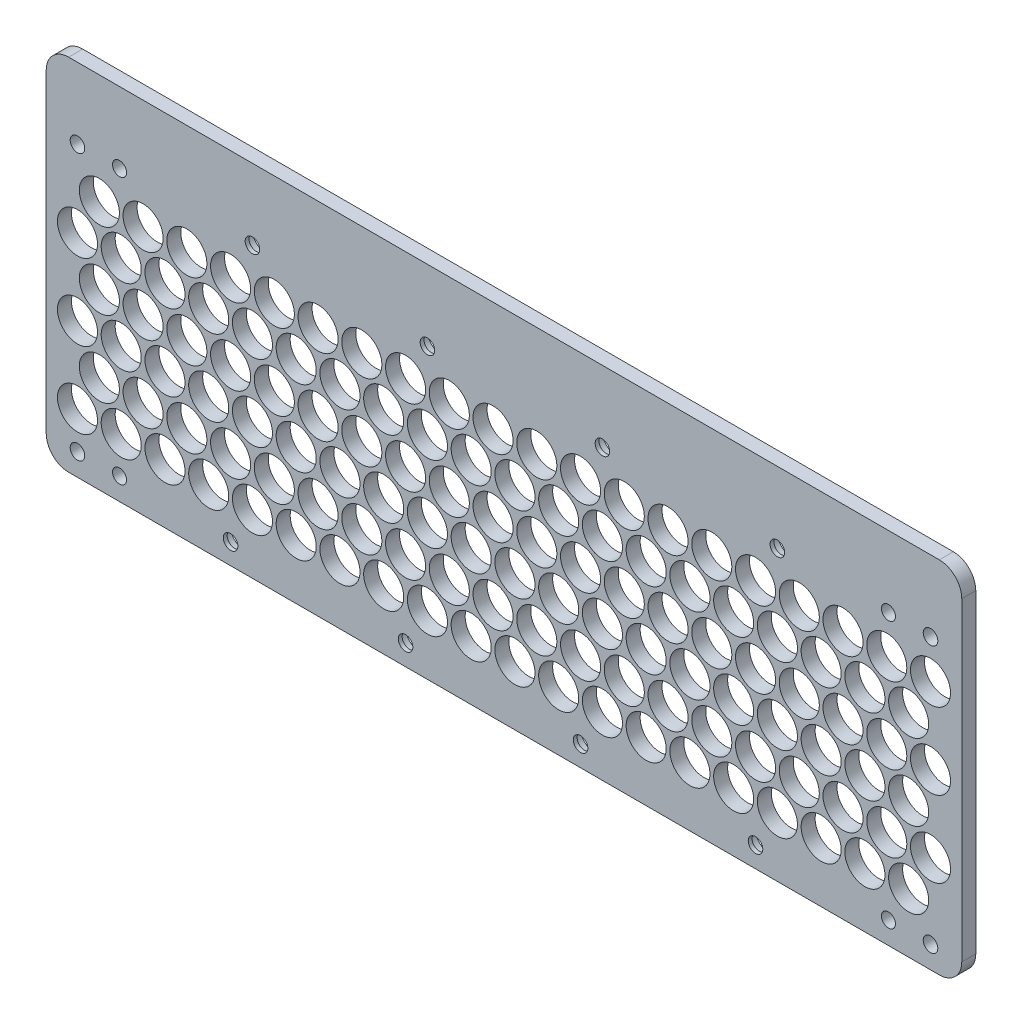
SolidWorks part; units mm, degrees
material "ABS"
ref_plane "X-Y Datum" through (0, 0, 0) normal (0, 0, 1) x (1, 0, 0)
ref_plane "X-Z Datum" through (0, 0, 0) normal (0, 1, 0) x (1, 0, 0)
ref_plane "Y-Z Datum" through (0, 0, 0) normal (1, 0, 0) x (0, 0, -1)
sketch "Sketch1" plane through (0, 0, 0) normal (0, 0, 1) x (1, 0, 0)
  line L0 (9.906, 17.1577) -> (0, 34.7553) construction
  line L1 (0, 34.7553) -> (0, 0) construction
  line L2 (0, -9.075) -> (0, -26.855) construction
  line L3 (-9.075, 0) -> (-14.155, 0) construction
  line L4 (386.334, 95.3207) -> (386.334, 113.1007) construction
  line L5 (395.409, 86.2457) -> (400.489, 86.2457) construction
  line L7 (-14.155, -26.855) -> (400.489, -26.855)
  line L8 (-14.155, -26.855) -> (-14.155, 113.1007)
  line L9 (-14.155, 113.1007) -> (400.489, 113.1007)
  line L10 (400.489, -26.855) -> (400.489, 113.1007)
  circle A0 centre (0, 0) radius 9.075
  circle A1 centre (19.812, 0) radius 9.075
  circle A2 centre (39.624, 0) radius 9.075
  circle A3 centre (59.436, 0) radius 9.075
  circle A4 centre (79.248, 0) radius 9.075
  circle A5 centre (99.06, 0) radius 9.075
  circle A6 centre (118.872, 0) radius 9.075
  circle A7 centre (138.684, 0) radius 9.075
  circle A8 centre (158.496, 0) radius 9.075
  circle A9 centre (178.308, 0) radius 9.075
  circle A10 centre (198.12, 0) radius 9.075
  circle A11 centre (217.932, 0) radius 9.075
  circle A12 centre (237.744, 0) radius 9.075
  circle A13 centre (257.556, 0) radius 9.075
  circle A14 centre (277.368, 0) radius 9.075
  circle A15 centre (297.18, 0) radius 9.075
  circle A16 centre (316.992, 0) radius 9.075
  circle A17 centre (336.804, 0) radius 9.075
  circle A18 centre (356.616, 0) radius 9.075
  circle A19 centre (376.428, 0) radius 9.075
  circle A20 centre (29.718, 17.1577) radius 9.075
  circle A21 centre (49.53, 17.1577) radius 9.075
  circle A22 centre (69.342, 17.1577) radius 9.075
  circle A23 centre (89.154, 17.1577) radius 9.075
  circle A24 centre (108.966, 17.1577) radius 9.075
  circle A25 centre (128.778, 17.1577) radius 9.075
  circle A26 centre (148.59, 17.1577) radius 9.075
  circle A27 centre (168.402, 17.1577) radius 9.075
  circle A28 centre (188.214, 17.1577) radius 9.075
  circle A29 centre (208.026, 17.1577) radius 9.075
  circle A30 centre (227.838, 17.1577) radius 9.075
  circle A31 centre (247.65, 17.1577) radius 9.075
  circle A32 centre (267.462, 17.1577) radius 9.075
  circle A33 centre (287.274, 17.1577) radius 9.075
  circle A34 centre (307.086, 17.1577) radius 9.075
  circle A35 centre (326.898, 17.1577) radius 9.075
  circle A36 centre (346.71, 17.1577) radius 9.075
  circle A37 centre (366.522, 17.1577) radius 9.075
  circle A38 centre (386.334, 17.1577) radius 9.075
  circle A39 centre (9.906, 17.1577) radius 9.075
  circle A40 centre (0, 34.544) radius 9.075
  circle A41 centre (19.812, 34.544) radius 9.075
  circle A42 centre (39.624, 34.544) radius 9.075
  circle A43 centre (59.436, 34.544) radius 9.075
  circle A44 centre (79.248, 34.544) radius 9.075
  circle A45 centre (99.06, 34.544) radius 9.075
  circle A46 centre (118.872, 34.544) radius 9.075
  circle A47 centre (138.684, 34.544) radius 9.075
  circle A48 centre (158.496, 34.544) radius 9.075
  circle A49 centre (178.308, 34.544) radius 9.075
  circle A50 centre (198.12, 34.544) radius 9.075
  circle A51 centre (217.932, 34.544) radius 9.075
  circle A52 centre (237.744, 34.544) radius 9.075
  circle A53 centre (257.556, 34.544) radius 9.075
  circle A54 centre (277.368, 34.544) radius 9.075
  circle A55 centre (297.18, 34.544) radius 9.075
  circle A56 centre (316.992, 34.544) radius 9.075
  circle A57 centre (336.804, 34.544) radius 9.075
  circle A58 centre (356.616, 34.544) radius 9.075
  circle A59 centre (376.428, 34.544) radius 9.075
  circle A60 centre (29.718, 51.7017) radius 9.075
  circle A61 centre (49.53, 51.7017) radius 9.075
  circle A62 centre (69.342, 51.7017) radius 9.075
  circle A63 centre (89.154, 51.7017) radius 9.075
  circle A64 centre (108.966, 51.7017) radius 9.075
  circle A65 centre (128.778, 51.7017) radius 9.075
  circle A66 centre (148.59, 51.7017) radius 9.075
  circle A67 centre (168.402, 51.7017) radius 9.075
  circle A68 centre (188.214, 51.7017) radius 9.075
  circle A69 centre (208.026, 51.7017) radius 9.075
  circle A70 centre (227.838, 51.7017) radius 9.075
  circle A71 centre (247.65, 51.7017) radius 9.075
  circle A72 centre (267.462, 51.7017) radius 9.075
  circle A73 centre (287.274, 51.7017) radius 9.075
  circle A74 centre (307.086, 51.7017) radius 9.075
  circle A75 centre (326.898, 51.7017) radius 9.075
  circle A76 centre (346.71, 51.7017) radius 9.075
  circle A77 centre (366.522, 51.7017) radius 9.075
  circle A78 centre (386.334, 51.7017) radius 9.075
  circle A79 centre (9.906, 51.7017) radius 9.075
  circle A80 centre (0, 69.088) radius 9.075
  circle A81 centre (19.812, 69.088) radius 9.075
  circle A82 centre (39.624, 69.088) radius 9.075
  circle A83 centre (59.436, 69.088) radius 9.075
  circle A84 centre (79.248, 69.088) radius 9.075
  circle A85 centre (99.06, 69.088) radius 9.075
  circle A86 centre (118.872, 69.088) radius 9.075
  circle A87 centre (138.684, 69.088) radius 9.075
  circle A88 centre (158.496, 69.088) radius 9.075
  circle A89 centre (178.308, 69.088) radius 9.075
  circle A90 centre (198.12, 69.088) radius 9.075
  circle A91 centre (217.932, 69.088) radius 9.075
  circle A92 centre (237.744, 69.088) radius 9.075
  circle A93 centre (257.556, 69.088) radius 9.075
  circle A94 centre (277.368, 69.088) radius 9.075
  circle A95 centre (297.18, 69.088) radius 9.075
  circle A96 centre (316.992, 69.088) radius 9.075
  circle A97 centre (336.804, 69.088) radius 9.075
  circle A98 centre (356.616, 69.088) radius 9.075
  circle A99 centre (376.428, 69.088) radius 9.075
  circle A100 centre (29.718, 86.2457) radius 9.075
  circle A101 centre (49.53, 86.2457) radius 9.075
  circle A102 centre (69.342, 86.2457) radius 9.075
  circle A103 centre (89.154, 86.2457) radius 9.075
  circle A104 centre (108.966, 86.2457) radius 9.075
  circle A105 centre (128.778, 86.2457) radius 9.075
  circle A106 centre (148.59, 86.2457) radius 9.075
  circle A107 centre (168.402, 86.2457) radius 9.075
  circle A108 centre (188.214, 86.2457) radius 9.075
  circle A109 centre (208.026, 86.2457) radius 9.075
  circle A110 centre (227.838, 86.2457) radius 9.075
  circle A111 centre (247.65, 86.2457) radius 9.075
  circle A112 centre (267.462, 86.2457) radius 9.075
  circle A113 centre (287.274, 86.2457) radius 9.075
  circle A114 centre (307.086, 86.2457) radius 9.075
  circle A115 centre (326.898, 86.2457) radius 9.075
  circle A116 centre (346.71, 86.2457) radius 9.075
  circle A117 centre (366.522, 86.2457) radius 9.075
  circle A118 centre (386.334, 86.2457) radius 9.075
  circle A119 centre (9.906, 86.2457) radius 9.075
  dimension "D1" = 20
  dimension "D3" = 3
  dimension "D2" = 2
extrude "Boss-Extrude1" add sketch "Sketch1" along normal blind 6.35
fillet "Fillet1" radius 10.16 2 edges at (400.489, -26.855, 3.175) (-14.155, -26.855, 3.175)
sketch "Sketch2" plane through (0, 0, 0) normal (0, 0, -1) x (-1, 0, 0)
  line L0 (-317.823, 86.2457) -> (-316.161, 86.2457) construction
  line L1 (-316.992, 103.7759) -> (-237.744, 103.7759) construction
  line L2 (-237.744, 103.7759) -> (-158.496, 103.7759) construction
  line L3 (-158.496, 103.7759) -> (-79.248, 103.7759) construction
  line L4 (-400.489, 48.2028) -> (14.155, 48.2028) construction
  line L5 (-316.992, 86.2457) -> (-316.992, 103.7759) construction
  line L6 (-193.167, 48.2028) -> (-193.167, 137.7249) construction
  line L7 (-68.511, 0) -> (-70.173, 0) construction
  line L8 (-238.575, 86.2457) -> (-236.913, 86.2457) construction
  line L9 (-237.744, 86.2457) -> (-237.744, 103.7759) construction
  line L10 (-159.327, 86.2457) -> (-157.665, 86.2457) construction
  line L11 (-158.496, 86.2457) -> (-158.496, 103.7759) construction
  line L12 (-80.079, 86.2457) -> (-78.417, 86.2457) construction
  line L13 (-79.248, 86.2457) -> (-79.248, 103.7759) construction
  line L14 (-307.917, 0) -> (-306.255, 0) construction
  line L15 (-307.086, 0) -> (-307.086, -17.5302) construction
  line L16 (-228.669, 0) -> (-227.007, 0) construction
  line L17 (-227.838, 0) -> (-227.838, -17.5302) construction
  line L18 (-149.421, 0) -> (-147.759, 0) construction
  line L19 (-148.59, 0) -> (-148.59, -17.5302) construction
  line L20 (-69.342, 0) -> (-69.342, -17.5302) construction
  line L21 (-400.489, -16.695) -> (-400.489, 113.1007) construction
  line L22 (14.155, -16.695) -> (14.155, 113.1007) construction
  line L23 (-193.167, 48.2028) -> (-193.167, -26.855) construction
  line L24 (3.995, -26.855) -> (-390.329, -26.855) construction
  line L26 (-386.334, 103.7759) -> (-386.334, -16.8023) construction
  line L27 (-386.334, 103.7759) -> (-400.489, 103.7759) construction
  line L28 (-400.489, 103.7759) -> (-400.489, 113.1007) construction
  circle A1 centre (-59.436, 0) radius 9.075 construction
  circle A2 centre (-79.248, 0) radius 9.075 construction
  circle A3 centre (-326.898, 86.2457) radius 9.075 construction
  circle A4 centre (-307.086, 86.2457) radius 9.075 construction
  circle A5 centre (-247.65, 86.2457) radius 9.075 construction
  circle A6 centre (-227.838, 86.2457) radius 9.075 construction
  circle A7 centre (-168.402, 86.2457) radius 9.075 construction
  circle A8 centre (-148.59, 86.2457) radius 9.075 construction
  circle A9 centre (-89.154, 86.2457) radius 9.075 construction
  circle A10 centre (-69.342, 86.2457) radius 9.075 construction
  circle A11 centre (-316.992, 0) radius 9.075 construction
  circle A12 centre (-297.18, 0) radius 9.075 construction
  circle A13 centre (-237.744, 0) radius 9.075 construction
  circle A14 centre (-217.932, 0) radius 9.075 construction
  circle A15 centre (-158.496, 0) radius 9.075 construction
  circle A16 centre (-138.684, 0) radius 9.075 construction
  point P4 (-316.992, 103.7759)
  point P26 (-386.334, 103.7759)
  point P34 (-69.342, -17.5302)
  point P41 (-227.838, -17.5302)
  point P42 (-148.59, -17.5302)
  point P43 (-307.086, -17.5302)
  point P102 (0, -16.8023)
  point P103 (-386.334, -16.8023)
  point P105 (0, 103.7759)
  dimension "D1" = 17.5302
hole_wizard "CBORE for M6 Pan Head Machine Screw1" positions "Sketch5" profile "Sketch6" counterbore size "M6" standard "ANSI Metric" end condition through all
sketch "Sketch5" plane through (0, 0, 0) normal (0, 0, -1) x (-1, 0, 0)
  point P24 (-148.59, -17.5302)
  point P27 (-227.838, -17.5302)
  point P30 (-307.086, -17.5302)
  point P38 (-316.992, 103.7759)
  point P41 (-237.744, 103.7759)
  point P45 (-158.496, 103.7759)
  point P49 (-79.248, 103.7759)
  point P60 (-69.342, -17.5302)
sketch "Sketch6" plane through (148.59, -17.5302, 0) normal (1, 0, 0) x (0, 1, 0)
  line L0 (0, 0) -> (0, 6.35)
  line L1 (0, 6.35) -> (3.3, 6.35)
  line L3 (3.3, 6.35) -> (3.3, 4.6)
  line L4 (3.3, 4.6) -> (6.5, 4.6)
  line L5 (6.5, 4.6) -> (6.5, 0)
  line L7 (6.5, 0) -> (0, 0)
  line L11 (0, -6.35) -> (0, 107.95) construction
  dimension "Thru Hole Dia." = 6.6
  dimension "Thru Hole Depth" = 6.35
  dimension "C'Bore Dia." = 13
  dimension "C'Bore Depth" = 4.6
sketch "Sketch7" plane through (0, 0, 0) normal (0, 0, -1) x (-1, 0, 0)
  line L0 (-400.489, -16.695) -> (-400.489, 113.1007) construction
  line L1 (-400.489, 135.9607) -> (-400.489, 113.1007)
  line L4 (-400.489, 135.9607) -> (14.155, 135.9607)
  line L6 (14.155, 113.1007) -> (-400.489, 113.1007) construction
  line L7 (14.155, 135.9607) -> (14.155, 113.1007)
  line L8 (-400.489, 113.1007) -> (14.155, 113.1007)
  dimension "D1" = 22.86
extrude "Boss-Extrude3" add sketch "Sketch7" against normal up to surface (6.35 mm away) up to face at (145.29, -17.5302, 6.35)
fillet "Fillet2" radius 10.16 2 edges at (-14.155, 135.9607, 3.175) (400.489, 135.9607, 3.175)
sketch "Sketch11" plane through (0, 0, 0) normal (0, 0, -1) x (-1, 0, 0)
  line L0 (-389.7253, 0) -> (-389.7253, -11.6663) construction
  line L1 (-372.1191, 17.3777) -> (-372.1191, 26.9679)
  line L2 (-376.428, 0) -> (-376.428, -5.2677) construction
  line L3 (-399.8844, 17.3777) -> (-399.8844, 29.0226)
  line L4 (-382.7347, 17.3777) -> (-382.7347, 29.0226)
  line L5 (-369.5649, 0) -> (-369.5649, 11.5769)
  line L6 (-352.8058, 0) -> (-352.8058, 11.5769)
  line L7 (-389.7253, 35.1084) -> (-389.7253, 24.2896)
  line L8 (-372.6508, 35.1084) -> (-372.6508, 24.2896)
  line L9 (-372.6508, -11.6663) -> (-406.2377, -11.6663)
  line L10 (-372.6508, 0) -> (-372.6508, -11.6663) construction
  line L12 (-399.8844, 52.0099) -> (-399.8844, 64.1334)
  line L13 (-382.7347, 52.0099) -> (-382.7347, 64.1334)
  line L14 (-406.2377, 26.9679) -> (-372.6508, 26.9679)
  line L16 (-389.7253, 69.3456) -> (-389.7253, 57.338)
  line L17 (-372.6508, 69.3456) -> (-372.6508, 57.338)
  line L18 (-406.2377, 61.3271) -> (-372.6508, 61.3271)
  line L19 (-379.2647, 17.3777) -> (-379.2647, 6.0914)
  line L20 (-362.5333, 17.3777) -> (-362.5333, 6.0914)
  line L21 (-370.526, 17.3777) -> (-370.526, 26.9679)
  line L22 (-370.526, 26.9679) -> (-372.6508, 26.9679)
  line L23 (-362.5333, 34.798) -> (-362.5333, 26.9679)
  line L24 (-362.051, 0) -> (-362.051, -11.6663)
  line L25 (-360.5787, 0) -> (-360.5787, -11.6663)
  line L26 (-372.6508, -11.6663) -> (-353.3404, -11.6663)
  line L27 (-359.7953, 34.798) -> (-359.7953, 26.9679)
  line L28 (-370.526, 26.9679) -> (-359.7953, 26.9679)
  line L29 (-372.6508, 61.3271) -> (-362.146, 61.3271)
  line L30 (-371.6722, 52.0099) -> (-371.6722, 61.3271)
  line L31 (-370.526, 52.0099) -> (-370.526, 61.3271)
  line L32 (-362.146, 61.3271) -> (-358.7278, 61.3271)
  line L33 (-363.0201, 69.3456) -> (-363.0201, 61.3271)
  line L34 (-360.5787, 69.3456) -> (-360.4369, 61.3271)
  line L35 (-369.5649, 35.1084) -> (-369.5649, 47.1539)
  line L36 (-352.8058, 35.1084) -> (-352.8058, 47.1539)
  line L37 (-379.2647, 52.0099) -> (-379.2647, 40.4497)
  line L38 (-363.0201, 52.0099) -> (-363.0201, 40.4497)
  line L39 (-369.5649, 69.3456) -> (-369.5649, 80.9994)
  line L40 (-352.8058, 69.3456) -> (-352.8058, 80.9994)
  line L41 (-341.6912, 0) -> (-341.6912, 11.5769)
  line L42 (-340.6574, 0) -> (-340.6574, 11.5769)
  line L43 (-351.7167, 17.3777) -> (-351.7167, 5.5163)
  line L44 (-350.7629, 17.3777) -> (-350.7629, 5.5163)
  line L45 (-341.6912, 35.1084) -> (-341.6912, 47.1539)
  line L46 (-340.6574, 35.1084) -> (-340.6574, 47.1539)
  line L47 (-351.7167, 52.0099) -> (-351.7167, 40.4497)
  line L48 (-350.1794, 52.0099) -> (-350.1794, 40.4497)
  line L49 (-342.56, 69.9146) -> (-342.56, 80.9994)
  line L50 (-340.6574, 69.9146) -> (-340.6574, 80.9994)
  line L51 (-379.2647, 9.088) -> (-340.6574, 8.2163)
  line L52 (-340.6574, 44.8641) -> (-369.5649, 44.8641)
  line L53 (-340.6574, 79.1885) -> (-369.5649, 79.1885)
  line L54 (-369.5649, 44.8641) -> (-379.2647, 44.8641)
  line L55 (-381.8268, 0) -> (-381.8268, 4.8492)
  line L56 (-380.6092, 0) -> (-380.6092, 4.8492)
  line L57 (-392.029, 17.3777) -> (-392.029, 12.8268)
  line L58 (-390.6416, 17.3777) -> (-390.6416, 12.8268)
  line L59 (-382.1743, 35.1084) -> (-382.1743, 41.6507)
  line L60 (-380.6092, 35.1084) -> (-380.6092, 41.6507)
  line L61 (-392.029, 52.0099) -> (-392.029, 45.9908)
  line L62 (-390.6416, 52.0099) -> (-390.6416, 45.9908)
  line L63 (-382.1743, 69.3456) -> (-382.1743, 75.8747)
  line L64 (-381.254, 69.3456) -> (-380.6092, 75.8747)
  circle A1 centre (-376.428, 0) radius 3.6
  circle A3 centre (-376.428, 0) radius 7.775
  circle A4 centre (-376.428, 0) radius 7.775
  circle A7 centre (-356.616, 0) radius 7.775
  circle A8 centre (-356.616, 0) radius 7.775
  circle A12 centre (-336.804, 0) radius 9.075 construction
  dimension "D1" = 1.3
  dimension "D2" = 1.3
sketch "Sketch12" plane through (0, 0, 0) normal (0, 0, -1) x (-1, 0, 0)
  line L2 (-389.7253, -5.3325) -> (-361.188, -5.3325)
  line L3 (-393.6268, 8.469) -> (-411.024, 17.3777)
  line L4 (-411.024, 17.3777) -> (-393.6268, 40.8588)
  line L5 (-393.6268, 40.8588) -> (-411.9147, 63.4861)
  line L6 (-411.9147, 63.4861) -> (-392.6657, 74.5919)
  line L7 (-372.6508, -11.6663) -> (-353.3404, -11.6663) construction
  line L8 (-389.7253, -18.0001) -> (-361.188, -18.0001)
  circle A1 centre (-389.7253, -11.6663) radius 6.3338
  circle A6 centre (-387.9351, 43.1007) radius 6.1173
  circle A7 centre (-386.3218, 75.8747) radius 6.4723
  circle A8 centre (-387.2798, 8.469) radius 6.3469
  circle A10 centre (-361.188, -11.6663) radius 6.3338
sketch "Sketch13" plane through (0, 0, 0) normal (0, 0, -1) x (-1, 0, 0)
  line L0 (-376.428, -16.7) -> (-299.9767, -16.7)
  line L9 (-376.428, -3.7) -> (-376.428, -16.7)
  line L10 (-299.9767, -16.7) -> (-299.9767, -3.7)
  line L11 (-376.428, -3.7) -> (-299.9767, -3.7)
  line L12 (-386.334, 13.6777) -> (-386.334, 3.6777)
  line L13 (-386.334, 3.6777) -> (-299.9767, 3.6777)
  line L14 (-299.9767, 3.6777) -> (-299.9767, 13.6777)
  line L15 (-386.334, 13.6777) -> (-299.9767, 13.6777)
  line L17 (-376.428, 31.098) -> (-299.9767, 31.098)
  line L18 (-376.428, 31.098) -> (-376.428, 21.0777)
  line L19 (-376.428, 21.0777) -> (-299.9767, 21.0777)
  line L20 (-299.9767, 31.098) -> (-299.9767, 21.0777)
  line L21 (-386.334, 48.4757) -> (-299.9767, 48.4757)
  line L22 (-386.334, 48.4757) -> (-386.334, 38.498)
  line L23 (-386.334, 38.498) -> (-299.9767, 38.498)
  line L24 (-299.9767, 48.4757) -> (-299.9767, 38.498)
  line L25 (-376.428, 65.896) -> (-300.032, 65.896)
  line L26 (-376.428, 65.896) -> (-376.428, 57.0303)
  line L27 (-376.428, 57.0303) -> (-300.032, 57.0303)
  line L28 (-300.032, 65.896) -> (-300.032, 57.0303)
  line L33 (-395.1886, 84.258) -> (-300.032, 84.258)
  line L34 (-395.1886, 84.258) -> (-395.1886, 73.296)
  line L35 (-395.1886, 73.296) -> (-300.032, 73.296)
  line L36 (-300.032, 84.258) -> (-300.032, 73.296)
  line L37 (-383.0915, 86.9737) -> (-383.0915, 79.0844)
  line L38 (-383.0915, 69.596) -> (-379.9062, 61.3147)
  line L39 (-379.1466, 70.1767) -> (-377.7962, 63.0027)
  line L40 (-389.781, 69.596) -> (-389.781, 75.4939)
  line L41 (-373.5762, 70.1767) -> (-373.5762, 75.4939)
  line L42 (-383.0915, 51.0859) -> (-378.312, 59.4647)
  line L43 (-399.5735, 52.1757) -> (-380.3229, 59.4647)
  line L44 (-392.9775, 52.1757) -> (-389.781, 44.2182)
  line L45 (-389.781, 53.041) -> (-387.8653, 45.2077)
  line L46 (-389.781, 34.798) -> (-389.781, 41.0155)
  line L47 (-373.5762, 34.798) -> (-373.5762, 41.6272)
  line L48 (-383.0915, 34.2108) -> (-378.4297, 25.6925)
  line L49 (-379.9062, 35.8164) -> (-376.7069, 28.4)
  line L50 (-383.0915, 17.3777) -> (-375.3927, 22.7378)
  line L51 (-399.5735, 17.3777) -> (-379.9062, 24.299)
  line L52 (-392.9775, 17.3777) -> (-389.781, 9.8105)
  line L53 (-389.781, 17.3777) -> (-386.9461, 11.7465)
  line L54 (-389.781, 0) -> (-390.535, 5.9906)
  line L55 (-372.8382, 0) -> (-372.8382, 6.9532)
  line L56 (-382.39, 0) -> (-379.9062, -10.8917)
  line L57 (-380.3229, 0) -> (-376.7069, -10.8917)
  line L58 (-392.4882, 86.9737) -> (-392.4882, 93.4619)
  line L59 (-401.2644, 90.6737) -> (-300.032, 90.6737)
  line L60 (-401.2644, 90.6737) -> (-401.2644, 99.6011)
  line L61 (-401.2644, 99.6011) -> (-300.032, 99.6011)
  line L62 (-300.032, 90.6737) -> (-300.032, 99.6011)
  line L63 (-389.781, 86.9737) -> (-389.3573, 93.1435)
  line L64 (-299.0393, 86.9737) -> (-297.9762, 96.324)
  line L65 (-299.9767, -16.7) -> (-191.4504, -16.7)
  line L66 (-299.9767, -16.7) -> (-299.9767, -3.7)
  line L67 (-299.9767, -3.7) -> (-191.4504, -3.7)
  line L68 (-191.4504, -16.7) -> (-191.4504, -3.7)
  line L69 (-299.0393, 99.6011) -> (-180.9676, 99.6011)
  line L70 (-299.0393, 99.6011) -> (-299.0393, 91.7087)
  line L71 (-299.0393, 91.7087) -> (-180.9676, 91.7087)
  line L72 (-180.9676, 99.6011) -> (-180.9676, 91.7087)
  line L73 (-283.4366, 86.9737) -> (-282.1903, 96.324)
  line L74 (-395.1886, 84.258) -> (-395.1886, 84.7737)
  line L75 (-401.2644, 90.6737) -> (-401.2644, 89.1737)
  circle A0 centre (-356.616, 0) radius 3.7
  circle A1 centre (-376.428, 0) radius 3.7
  circle A2 centre (-376.428, 0) radius 7.775
  circle A3 centre (-376.428, 0) radius 7.775
  circle A4 centre (-386.334, 51.7017) radius 3.226
  circle A5 centre (-386.334, 17.1577) radius 3.48
  circle A6 centre (-376.428, 69.088) radius 3.192
  circle A7 centre (-386.334, 86.2457) radius 3.7
  circle A8 centre (-376.428, 34.544) radius 3.446
  circle A9 centre (-386.334, 86.2457) radius 9.075 construction
  circle A12 centre (-376.428, 34.544) radius 9.075 construction
  circle A13 centre (-188.214, 86.2457) radius 9.075 construction
  dimension "D1" = 1.3
sketch "Sketch15" plane through (0, 0, 0) normal (0, 0, -1) x (-1, 0, 0)
  line L1 (-385.503, -3.7) -> (-288.0191, -3.7)
  line L2 (-385.503, -3.7) -> (-385.503, -14.7983)
  line L3 (-385.503, -14.7983) -> (-288.0191, -14.7983)
  line L4 (-288.0191, -3.7) -> (-288.0191, -14.7983)
  line L5 (-286.443, -3.7) -> (-189.045, -3.7)
  line L6 (-286.443, -3.7) -> (-286.443, -14.7983)
  line L7 (-286.443, -14.7983) -> (-189.045, -14.7983)
  line L8 (-189.045, -3.7) -> (-189.045, -14.7983)
  line L9 (-395.409, 13.4577) -> (-298.011, 13.4577)
  line L10 (-395.409, 13.4577) -> (-395.409, 3.7)
  line L11 (-395.409, 3.7) -> (-298.011, 3.7)
  line L12 (-298.011, 13.4577) -> (-298.011, 3.7)
  circle A0 centre (-376.428, 0) radius 3.7
  circle A1 centre (-386.334, 17.1577) radius 3.7
  circle A4 centre (-376.428, 0) radius 7.775
  circle A5 centre (-376.428, 0) radius 7.775
  dimension "D1" = 1.3
sketch "Sketch16" plane through (0, 0, 0) normal (0, 0, -1) x (-1, 0, 0)
  line L1 (-395.409, -9.075) -> (9.0886, -9.075)
  line L2 (-395.409, -9.075) -> (-395.409, 95.3207)
  line L3 (-395.409, 95.3207) -> (9.0886, 95.3207)
  line L4 (9.0886, -9.075) -> (9.0886, 95.3207)
hole_wizard "M6 Clearance Hole1" positions "Sketch17" profile "Sketch18" hole size "M6" standard "ANSI Metric" end condition through all
sketch "Sketch17" plane through (0, 0, 0) normal (0, 0, -1) x (-1, 0, 0)
  point P0 (-386.334, 103.7759)
  point P3 (-386.334, -16.8023)
  point P6 (0, 103.7759)
  point P9 (0, -16.8023)
sketch "Sketch18" plane through (386.334, 103.7759, 0) normal (1, 0, 0) x (0, 1, 0)
  line L0 (0, 0) -> (0, 6.35)
  line L1 (0, 6.35) -> (3.3, 6.35)
  line L2 (3.3, 6.35) -> (3.3, 0)
  line L5 (3.3, 0) -> (0, 0)
  line L11 (0, -6.35) -> (0, 107.95) construction
  dimension "Thru Hole Dia." = 6.6
  dimension "Thru Hole Depth" = 6.35
sketch "Sketch19" plane through (0, 0, 0) normal (0, 0, -1) x (-1, 0, 0)
  line L0 (-386.334, 103.7759) -> (-367.284, 103.7759) construction
  line L1 (-386.334, -16.8023) -> (-367.284, -16.8023) construction
  line L2 (-193.167, 163.3949) -> (-193.167, -39.5015) construction
  line L3 (14.155, -16.695) -> (14.155, 125.8007) construction
  line L4 (-400.489, -26.855) -> (14.155, -26.855) construction
  line L5 (-400.489, -26.855) -> (-400.489, 109.2518) construction
  line L6 (-400.489, 109.2518) -> (14.155, 109.2518) construction
  line L7 (14.155, -26.855) -> (14.155, 109.2518) construction
  line L8 (-367.284, 109.2518) -> (-367.284, 103.7759) construction
  circle A0 centre (-367.284, 103.7759) radius 3.175
  circle A1 centre (-367.284, -16.8023) radius 3.175
  circle A2 centre (-19.05, 103.7759) radius 3.175
  circle A3 centre (-19.05, -16.8023) radius 3.175
extrude "Cut-Extrude1" cut sketch "Sketch19" against normal through all
sketch "Sketch20" plane through (0, 0, 0) normal (0, 0, -1) x (-1, 0, 0)
  circle A0 centre (-366.522, 74.8492) radius 2.3215
